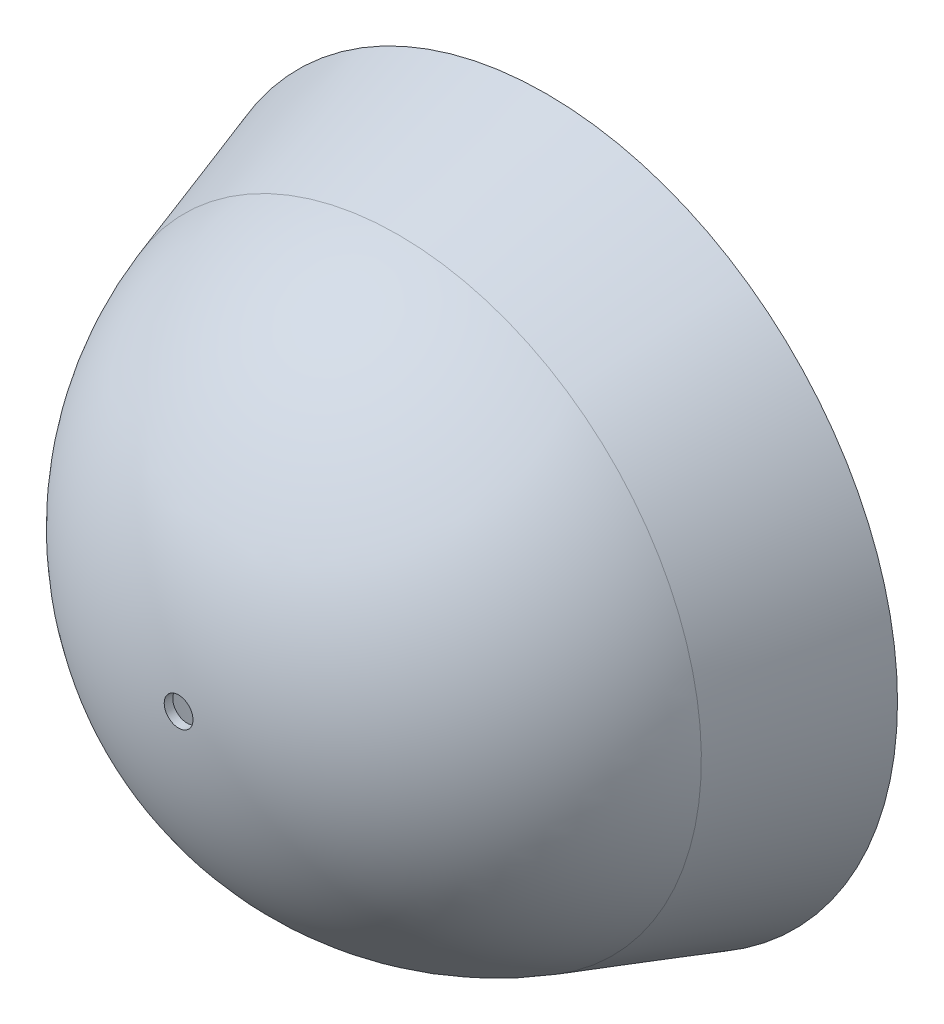
SolidWorks part; units mm, degrees
ref_plane "Front Plane" through (0, 0, 0) normal (0, 0, 1) x (1, 0, 0)
ref_plane "Top Plane" through (0, 0, 0) normal (0, 1, 0) x (1, 0, 0)
ref_plane "Right Plane" through (0, 0, 0) normal (1, 0, 0) x (0, 0, -1)
ref_axis "Axis1" through (0, 0, -134.3417) along (0, 0, 1)
sketch "Sketch1" plane through (0, 0, 0) normal (1, 0, 0) x (0, 0, -1)
  line L0 (-9.9608, 0) -> (-56.5616, 0) construction
  line L1 (51.6718, 75.4901) -> (94.811, 89.5069)
  line L6 (99.1988, 95.5461) -> (99.1988, 114.3)
  line L7 (52.6529, 72.4705) -> (174.4389, 112.0412) construction
  arc A0 (51.6718, 75.4901) -> (-3.175, 0) centre (76.2, 0) ccw
  arc A1 (94.811, 89.5069) -> (99.1988, 95.5461) centre (92.8488, 95.5461) ccw
  arc A3 (52.6529, 72.4705) -> (5.6757, -28.8576) centre (76.2, 0) ccw construction
  dimension "D1" = 79.375
  dimension "D2" = 179.0138
  dimension "D19" = 6.35
  dimension "D5" = 76.2
  dimension "D3" = 97.986
  dimension "D6" = 144.941
  dimension "D11" = 18
  dimension "D20" = 228.6
  dimension "D22" = 18
  dimension "D23" = 3.175
revolve "Revolve-Thin1" add sketch "Sketch1" angle 360 about axis through (0, 0, -134.3417) along (0, 0, 1) wall 2.1844
sketch "Sketch5" plane through (0, 0, 0) normal (1, 0, 0) x (0, 0, -1)
  line L2 (-8.255, 0) -> (-23.8864, 0)
  line L3 (88.9, 92.9277) -> (88.9, 73.6245)
  line L5 (93.2412, 94.3383) -> (50.102, 80.3215)
  line L7 (88.9, 92.9277) -> (50.102, 80.3215)
  line L8 (88.9, 73.6245) -> (116.2527, 73.6245)
  line L9 (116.2527, 73.6245) -> (116.2527, 127.2178)
  line L10 (116.2527, 127.2178) -> (-23.8864, 127.2178)
  line L11 (-23.8864, 127.2178) -> (-23.8864, 0)
  arc A2 (50.102, 80.3215) -> (-8.255, 0) centre (76.2, 0) ccw
  arc A3 (50.102, 80.3215) -> (-8.255, 0) centre (76.2, 0) ccw
  dimension "D2" = 92.075
  dimension "D1" = 5.08
revolve "Cut-Revolve1" cut sketch "Sketch5" angle 360 about axis through (0, 0, -134.3417) along (0, 0, 1)
sketch "Sketch2" plane through (0, 0, 0) normal (1, 0, 0) x (0, 0, -1)
  line L0 (191.1932, 41.4345) -> (77.3529, 0) construction
  line L1 (77.3529, 0) -> (191.1932, -41.4345) construction
  line L2 (191.1932, -41.4345) -> (191.1932, 41.4345) construction
  line L4 (8.89, 0.254) -> (124.8115, 0.254)
  line L5 (8.89, 0.254) -> (8.89, -0.254)
  line L6 (8.89, -0.254) -> (124.8115, -0.254)
  line L7 (124.8115, 0.254) -> (124.8115, -0.254)
  point P2 (191.1932, 0)
  point P9 (8.89, 0)
  dimension "D1" = 40
  dimension "D2" = 0.508
  dimension "D3" = 8.89
extrude "Cut-Extrude1" [suppressed] cut sketch "Sketch2" along normal blind 101.6
pattern_circular "CirPattern1" [suppressed] count 8 over 360 about axis through (0, 0, -134.3417) along (0, 0, 1)
sketch "Sketch3" plane through (0, 0, 0) normal (0, 0, 1) x (1, 0, 0)
  circle A0 centre (0, 0) radius 3.683
  dimension "D1" = 7.366
extrude "CE-00 Hole at center" cut sketch "Sketch3" against normal mid plane 25.4
